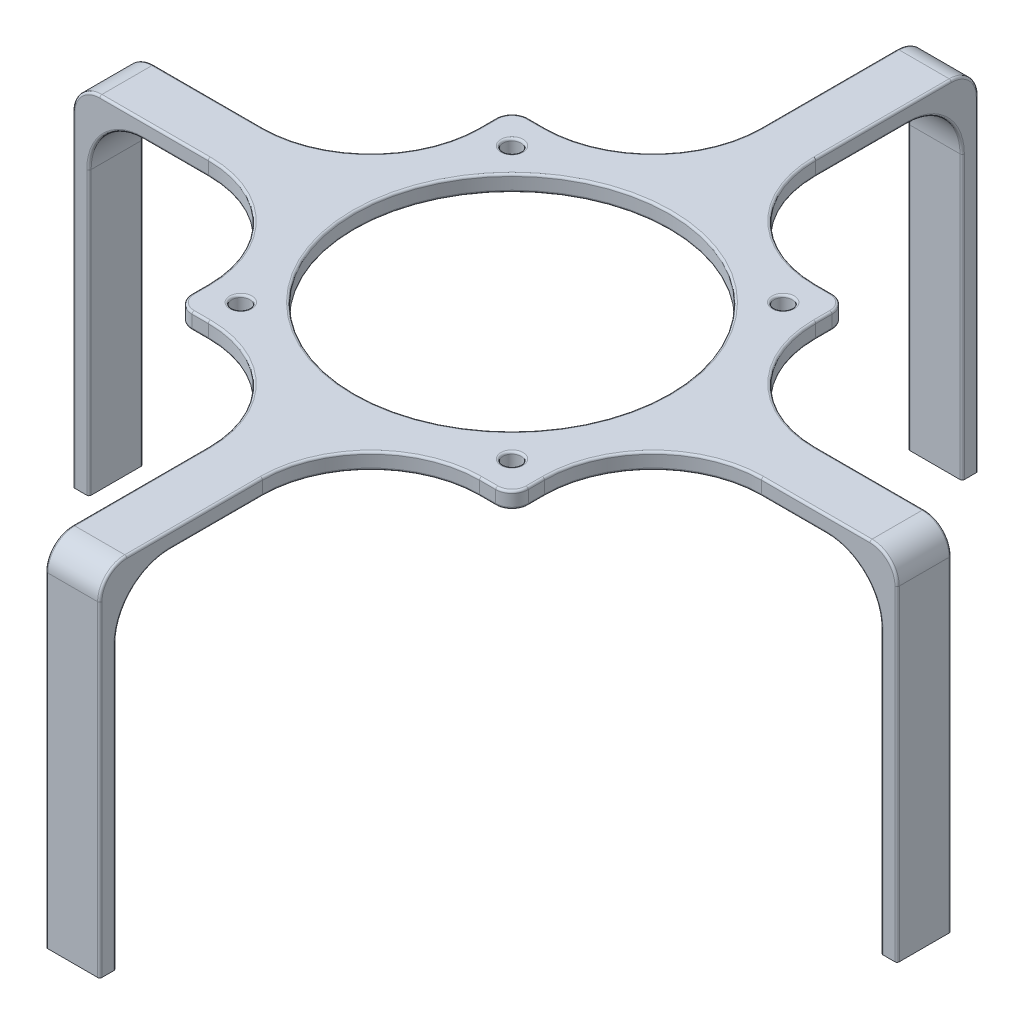
SolidWorks part; units mm, degrees
ref_plane "Front Plane" through (0, 0, 0) normal (0, 0, 1) x (1, 0, 0)
ref_plane "Top Plane" through (0, 0, 0) normal (0, 1, 0) x (1, 0, 0)
ref_plane "Right Plane" through (0, 0, 0) normal (1, 0, 0) x (0, 0, -1)
sketch "Sketch1" plane through (0, 0, 0) normal (0, 1, 0) x (1, 0, 0)
  line L1 (0, 0) -> (62, 0)
  line L2 (0, 0) -> (0, -62)
  line L3 (0, -62) -> (62, -62)
  line L4 (62, 0) -> (62, -62)
  dimension "D1" = 62
  dimension "D2" = 62
extrude "Boss-Extrude1" add sketch "Sketch1" along normal blind 3
sketch "Sketch2" plane through (0, 0, 0) normal (0, -1, 0) x (-1, 0, 0)
  circle A0 centre (-56, -56) radius 1.65
  circle A1 centre (-6, -56) radius 1.65
  circle A2 centre (-6, -6) radius 1.65
  circle A3 centre (-56, -6) radius 1.65
  circle A4 centre (-31, -31) radius 29
  dimension "D1" = 3.3
  dimension "D2" = 3.3
  dimension "D3" = 3.3
  dimension "D4" = 3.3
extrude "Cut-Extrude1" cut sketch "Sketch2" against normal blind 10
sketch "Sketch3" plane through (0, 3, 0) normal (0, 1, 0) x (1, 0, 0)
  line L0 (62, 0) -> (0, 0) construction
  line L1 (26, 0) -> (36, 0)
  line L2 (26, 0) -> (26, 50)
  line L3 (26, 50) -> (36, 50)
  line L4 (36, 0) -> (36, 50)
  line L5 (0, 0) -> (0, -62) construction
  line L6 (0, -26) -> (-45, -26)
  line L7 (0, -26) -> (0, -36)
  line L8 (0, -36) -> (-45, -36)
  line L9 (-45, -26) -> (-45, -36)
  line L20 (62, -62) -> (62, 0) construction
  line L21 (62, -26) -> (107, -26)
  line L22 (62, -26) -> (62, -36)
  line L23 (62, -36) -> (107, -36)
  line L24 (107, -26) -> (107, -36)
  line L25 (0, -62) -> (62, -62) construction
  line L26 (26, -62) -> (36, -62)
  line L27 (26, -62) -> (26, -112)
  line L28 (26, -112) -> (36, -112)
  line L29 (36, -62) -> (36, -112)
  point P24 (31, 0)
  point P25 (31, 0)
  point P26 (62, -31)
  point P27 (62, -31)
  point P28 (31, -62)
  point P29 (31, -62)
  point P30 (0, -31)
  point P31 (0, -31)
  dimension "D1" = 10
  dimension "D2" = 10
  dimension "D3" = 10
  dimension "D4" = 0
  dimension "D5" = 0
  dimension "D6" = 0
  dimension "D7" = 10
  dimension "D8" = 0
  dimension "D9" = 50
  dimension "D10" = 45
  dimension "D11" = 45
  dimension "D12" = 50
extrude "Boss-Extrude2" add sketch "Sketch3" against normal blind 3
sketch "Sketch4" plane through (0, 0, 0) normal (0, -1, 0) x (-1, 0, 0)
  line L20 (-26, 50) -> (-26, 0) construction
  line L21 (-36, 50) -> (-26, 50)
  line L22 (-36, 50) -> (-36, 47)
  line L23 (-36, 47) -> (-26, 47)
  line L24 (-26, 50) -> (-26, 47)
  line L25 (-107, -26) -> (-62, -26) construction
  line L26 (-107, -36) -> (-104, -36)
  line L27 (-107, -36) -> (-107, -26)
  line L28 (-107, -26) -> (-104, -26)
  line L29 (-104, -36) -> (-104, -26)
  line L30 (-26, -62) -> (-26, -112) construction
  line L31 (-36, -112) -> (-26, -112)
  line L32 (-36, -112) -> (-36, -109)
  line L33 (-36, -109) -> (-26, -109)
  line L34 (-26, -112) -> (-26, -109)
  line L35 (0, -26) -> (45, -26) construction
  line L36 (45, -36) -> (42, -36)
  line L37 (45, -36) -> (45, -26)
  line L38 (45, -26) -> (42, -26)
  line L39 (42, -36) -> (42, -26)
  dimension "D1" = 3
  dimension "D2" = 3
  dimension "D3" = 3
  dimension "D4" = 3
extrude "Boss-Extrude3" add sketch "Sketch4" along normal blind 62
fillet "Fillet2" radius 10 4 edges at (31, 0, 109) (-42, 0, 31) (31, 0, -47) (104, 0, 31)
fillet "Fillet3" radius 5 4 edges at (107, 3, 31) (31, 3, 112) (-45, 3, 31) (31, 3, -50)
fillet "Fillet1" radius 20 8 edges at (36, 1.5, 0) (26, 1.5, 0) (0, 1.5, 26) (0, 1.5, 36) (26, 1.5, 62) (36, 1.5, 62) (62, 1.5, 26) (62, 1.5, 36)
fillet "Fillet4" radius 3 4 edges at (62, 1.5, 0) (62, 1.5, 62) (0, 1.5, 62) (0, 1.5, 0)
fillet "Fillet5" radius 0.4 49 edges at (36, -32, 112) (36, 1.5355, 110.5355) (107, -32, 36) (105.5355, 1.5355, 36) (-45, -32, 36) (-43.5355, 1.5355, 36) (26, -32, 112) (26, 1.5355, 110.5355) (26, -32, -50) (26, 1.5355, -48.5355) (-45, -32, 26) (-43.5355, 1.5355, 26) (107, -32, 26) (105.5355, 1.5355, 26) (36, -32, -50) (36, 1.5355, -48.5355) (67.8579, 3, 20.1421) (92, 3, 26) (92, 3, 36) (67.8579, 3, 41.8579) (62, 3, 57.5) (61.1213, 3, 61.1213) (57.5, 3, 62) (41.8579, 3, 67.8579) (36, 3, 94.5) (26, 3, 94.5) (20.1421, 3, 67.8579) (4.5, 3, 62) (0.8787, 3, 61.1213) (0, 3, 57.5) (-5.8579, 3, 41.8579) (-30, 3, 36) (-30, 3, 26) (-5.8579, 3, 20.1421) (0, 3, 4.5) (0.8787, 3, 0.8787) (4.5, 3, 0) (20.1421, 3, -5.8579) (26, 3, -32.5) (36, 3, -32.5) (41.8579, 3, -5.8579) (57.5, 3, 0) (61.1213, 3, 0.8787) (62, 3, 4.5) (56, 3, 57.65) (56, 3, 7.65) (31, 3, 60) (6, 3, 7.65) (6, 3, 57.65)
fillet "Fillet7" radius 0.4 49 edges at (26, -36, -47) (26, -2.9289, -44.0711) (-42, -36, 26) (-39.0711, -2.9289, 26) (-42, -36, 36) (-39.0711, -2.9289, 36) (26, -36, 109) (26, -2.9289, 106.0711) (36, -36, 109) (36, -2.9289, 106.0711) (104, -36, 36) (101.0711, -2.9289, 36) (104, -36, 26) (101.0711, -2.9289, 26) (36, -36, -47) (36, -2.9289, -44.0711) (41.8579, 0, -5.8579) (36, 0, -28.5) (26, 0, -28.5) (20.1421, 0, -5.8579) (4.5, 0, 0) (0.8787, 0, 0.8787) (0, 0, 4.5) (-5.8579, 0, 20.1421) (-26, 0, 26) (-26, 0, 36) (-5.8579, 0, 41.8579) (0, 0, 57.5) (0.8787, 0, 61.1213) (4.5, 0, 62) (20.1421, 0, 67.8579) (26, 0, 90.5) (36, 0, 90.5) (41.8579, 0, 67.8579) (57.5, 0, 62) (61.1213, 0, 61.1213) (62, 0, 57.5) (67.8579, 0, 41.8579) (88, 0, 36) (88, 0, 26) (67.8579, 0, 20.1421) (62, 0, 4.5) (61.1213, 0, 0.8787) (57.5, 0, 0) (56, 0, 54.35) (56, 0, 4.35) (31, 0, 2) (6, 0, 4.35) (6, 0, 54.35)
